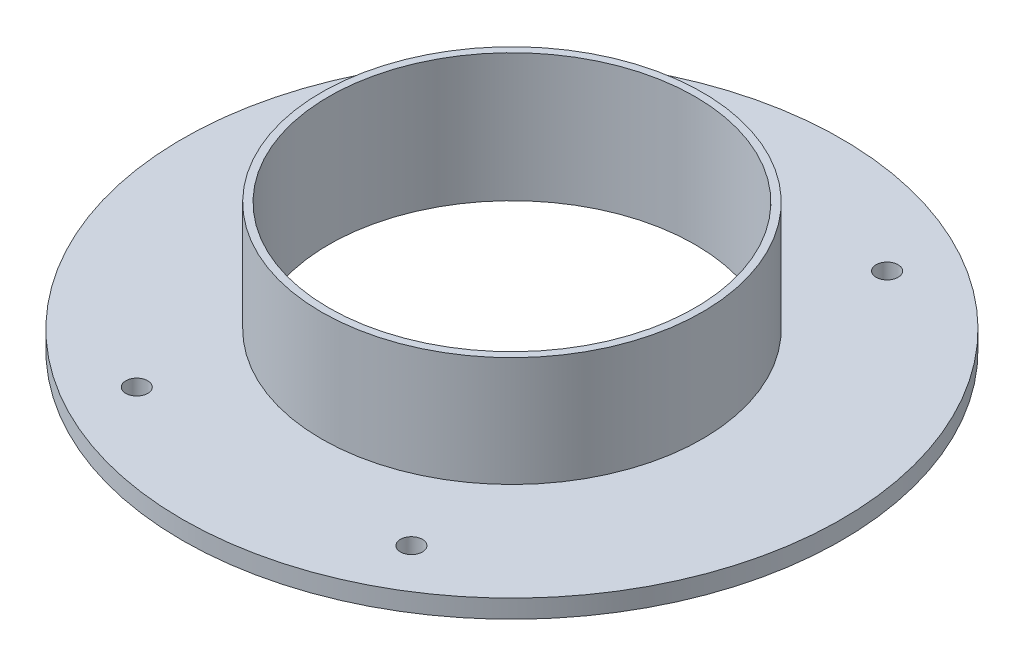
SolidWorks part; units mm, degrees
ref_plane "Front Plane" through (0, 0, 0) normal (0, 0, 1) x (1, 0, 0)
ref_plane "Top Plane" through (0, 0, 0) normal (0, 1, 0) x (1, 0, 0)
ref_plane "Right Plane" through (0, 0, 0) normal (1, 0, 0) x (0, 0, -1)
sketch "Sketch1" plane through (0, 0, 0) normal (0, 1, 0) x (1, 0, 0)
  line L0 (0, 0) -> (90, 0) construction
  line L2 (37.5, 64.9519) -> (0, 0) construction
  line L4 (0, 50) -> (0, -50) construction
  circle A0 centre (0, 0) radius 90
  circle A1 centre (0, 0) radius 50
  circle A2 centre (37.5, 64.9519) radius 3
  circle A3 centre (-37.5, 64.9519) radius 3
  circle A4 centre (37.5, -64.9519) radius 3
  circle A5 centre (-37.5, -64.9519) radius 3
  point P0 (0, 0)
  dimension "D1" = 180
  dimension "D2" = 100
  dimension "D3" = 6
  dimension "D4" = 60
  dimension "D5" = 75
extrude "Boss-Extrude1" add sketch "Sketch1" along normal blind 5
sketch "Sketch2" plane through (0, 5, 0) normal (0, 1, 0) x (1, 0, 0)
  circle A0 centre (0, 0) radius 50 construction
  circle A1 centre (0, 0) radius 50
  circle A2 centre (0, 0) radius 52
  dimension "D1" = 2
extrude "Boss-Extrude2" add sketch "Sketch2" along normal blind 30
